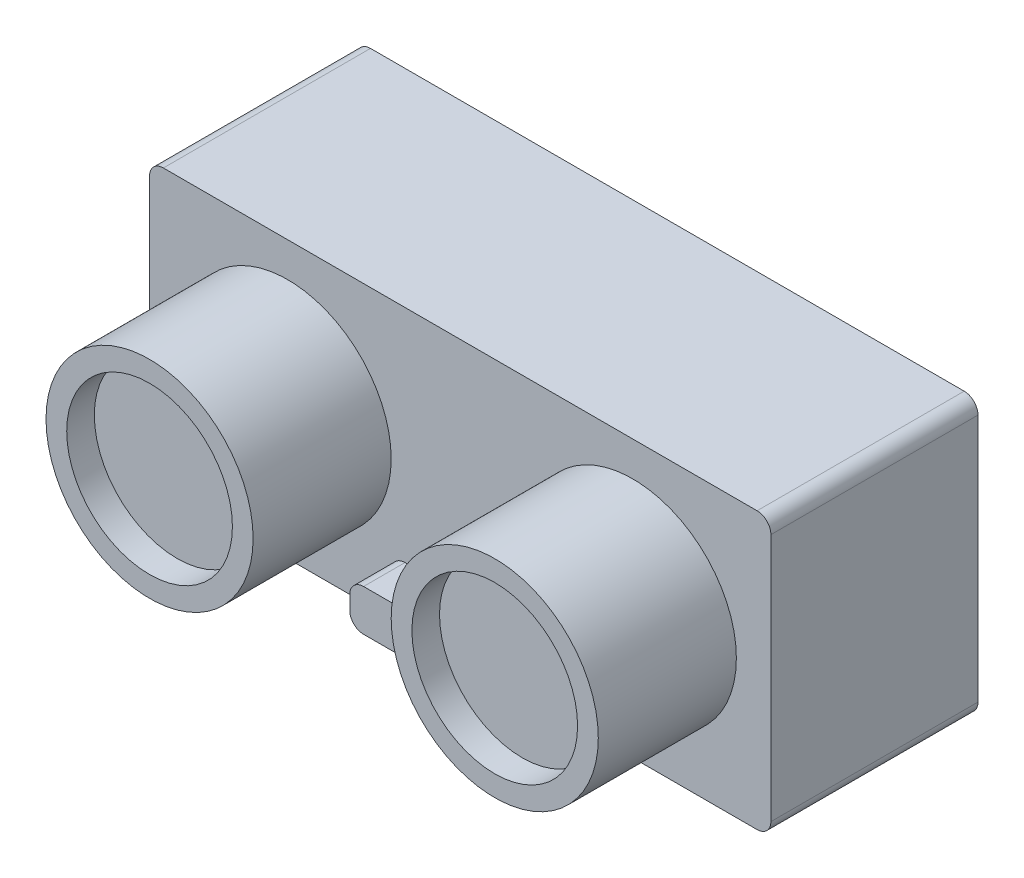
SolidWorks part; units mm, degrees
ref_plane "Front Plane" through (0, 0, 0) normal (0, 0, 1) x (1, 0, 0)
ref_plane "Top Plane" through (0, 0, 0) normal (0, 1, 0) x (1, 0, 0)
ref_plane "Right Plane" through (0, 0, 0) normal (1, 0, 0) x (0, 0, -1)
sketch "Sketch1" plane through (0, 0, 0) normal (0, 0, 1) x (1, 0, 0)
  line L1 (1, 0) -> (44, 0)
  line L2 (0, 1) -> (0, 19)
  line L3 (1, 20) -> (44, 20)
  line L4 (45, 1) -> (45, 19)
  arc A0 (44, 20) -> (45, 19) centre (44, 19) cw
  arc A1 (1, 0) -> (0, 1) centre (1, 1) cw
  arc A2 (44, 0) -> (45, 1) centre (44, 1) ccw
  arc A3 (0, 19) -> (1, 20) centre (1, 19) cw
  point P7 (45, 20)
  point P10 (0, 0)
  point P15 (0, 20)
  dimension "D3" = 1
  dimension "D1" = 20
  dimension "D2" = 45
extrude "Boss-Extrude1" add sketch "Sketch1" along normal blind 15
sketch "Sketch2" plane through (0, 0, 15) normal (0, 0, 1) x (1, 0, 0)
  line L0 (45, 1) -> (45, 19) construction
  line L1 (44, 20) -> (1, 20) construction
  circle A0 centre (10, 10) radius 7.5
  circle A1 centre (35, 10) radius 7.5
  point P4 (0, 0)
  dimension "D1" = 15
  dimension "D2" = 25
  dimension "D3" = 10
  dimension "D4" = 10
extrude "Boss-Extrude2" add sketch "Sketch2" along normal blind 10
sketch "Sketch3" plane through (0, 0, 25) normal (0, 0, 1) x (1, 0, 0)
  circle A0 centre (10, 10) radius 6
  circle A1 centre (35, 10) radius 6
  dimension "D1" = 12
extrude "Cut-Extrude1" cut sketch "Sketch3" against normal blind 2
sketch "Sketch4" plane through (0, 0, 15) normal (0, 0, 1) x (1, 0, 0)
  line L0 (1, 0) -> (44, 0) construction
  line L1 (18.5, 4) -> (26.5, 4)
  line L2 (17.5, 3) -> (17.5, 2)
  line L3 (18.5, 1) -> (26.5, 1)
  line L4 (27.5, 3) -> (27.5, 2)
  line L5 (45, 1) -> (45, 19) construction
  arc A0 (26.5, 4) -> (27.5, 3) centre (26.5, 3) cw
  arc A1 (26.5, 1) -> (27.5, 2) centre (26.5, 2) ccw
  arc A2 (17.5, 2) -> (18.5, 1) centre (18.5, 2) ccw
  arc A3 (18.5, 4) -> (17.5, 3) centre (18.5, 3) ccw
  point P10 (27.5, 4)
  point P15 (17.5, 1)
  point P18 (17.5, 4)
  dimension "D5" = 1
  dimension "D1" = 10
  dimension "D2" = 3
  dimension "D3" = 1
  dimension "D4" = 17.5
extrude "Boss-Extrude3" add sketch "Sketch4" along normal blind 3
